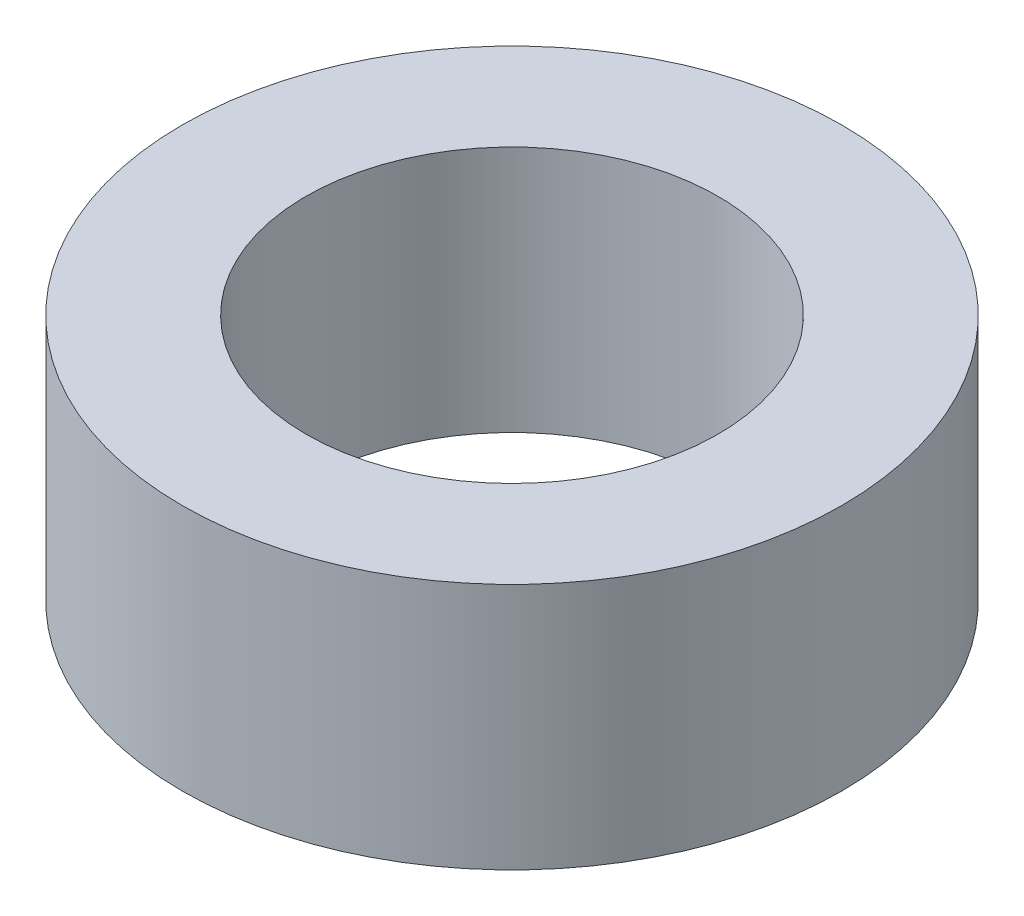
SolidWorks part; units mm, degrees
material "AISI 304"
ref_plane "前视基准面" through (0, 0, 0) normal (0, 0, 1) x (1, 0, 0)
ref_plane "上视基准面" through (0, 0, 0) normal (0, 1, 0) x (1, 0, 0)
ref_plane "右视基准面" through (0, 0, 0) normal (1, 0, 0) x (0, 0, -1)
other "Configuration Table"
sketch "草图1" plane through (0, 0, 0) normal (0, 1, 0) x (1, 0, 0)
  circle A0 centre (0, 0) radius 2.5
  circle A1 centre (0, 0) radius 4
  dimension "D1" = 5
  dimension "D2" = 8
extrude "凸台-拉伸1" add sketch "草图1" along normal blind 3
